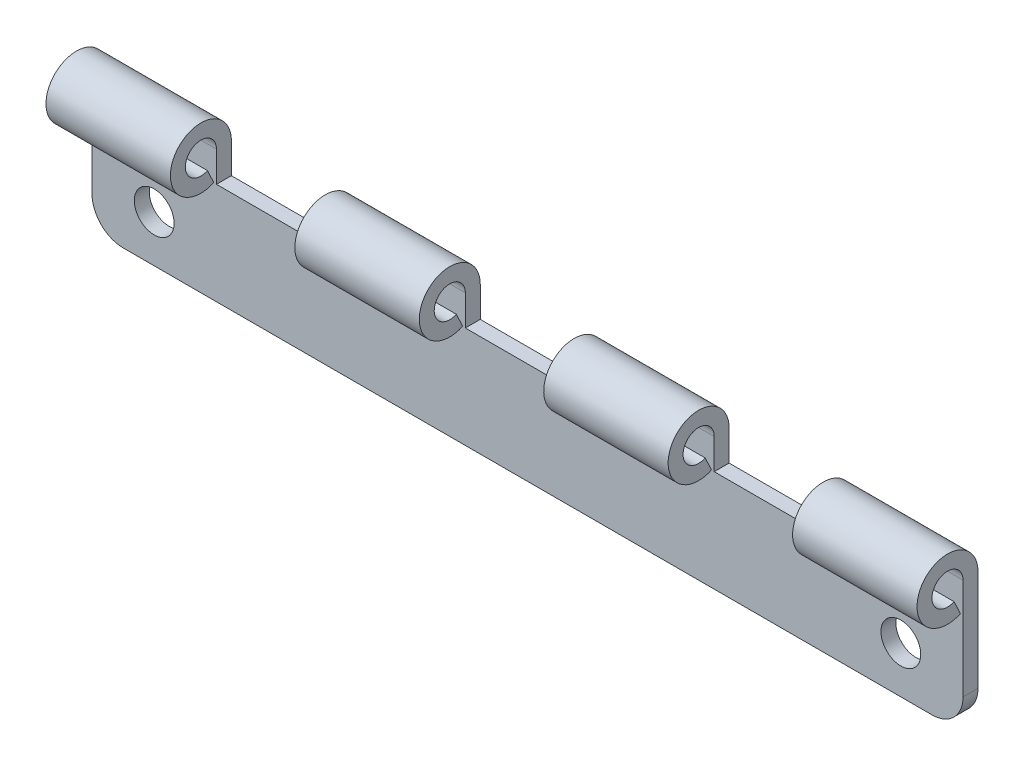
SolidWorks part; units mm, degrees
other "Top Leaf"
other "Bottom Leaf"
other "Pin" parameters "D1"=17.6771, "Angle"=25, "D2"=74.218, "Pin Diameter"=3.175, "D3"=51.2197, "Knuckle Diameter"=28.575, "Leaf Thickness"=1.524, "Overall Width"=26.9875, "Length"=609.6, "Break Line"=101.6, "Knuckle Length"=12.7, "Chamfer"=0.3175
ref_plane "Front Plane" through (0, 0, 0) normal (0, 0, 1) x (1, 0, 0)
ref_plane "Top Plane" through (0, 0, 0) normal (0, 1, 0) x (1, 0, 0)
ref_plane "Right Plane" through (0, 0, 0) normal (1, 0, 0) x (0, 0, -1)
sketch "Sketch1" plane through (0, 0, 0) normal (1, 0, 0) x (0, 0, -1)
  line L0 (3.1115, 0) -> (3.1115, -13.4937) construction
  line L1 (3.1115, -13.4937) -> (1.5875, -13.4937) construction
  line L2 (1.5875, -13.4937) -> (1.5875, -2.6761) construction
  line L3 (0, 1.5875) -> (0, 3.1115) construction
  line L4 (0.6709, 1.4388) -> (1.315, 2.82) construction
  line L5 (0, -1.5875) -> (0, -3.1115) construction
  line L6 (0.6709, -1.4388) -> (1.315, -2.82) construction
  line L7 (3.1115, 0) -> (3.1115, 13.4937) construction
  line L8 (3.1115, 13.4937) -> (1.5875, 13.4937) construction
  line L9 (1.5875, 13.4937) -> (1.5875, 2.6761) construction
  line L10 (0, 3.1115) -> (3.1115, 3.1115) construction
  line L11 (0, -3.1115) -> (3.1115, -3.1115) construction
  line L12 (1.5875, -2.6761) -> (1.5875, 2.6761) construction
  line L13 (1.5875, 3.1369) -> (3.1115, 3.1369) construction
  circle A0 centre (0, 0) radius 1.5875 construction
  circle A1 centre (0, 0) radius 3.1115 construction
  point P3 (0, 1.5875)
  point P4 (0, -1.5875)
  point P5 (-1.5875, 0)
  point P6 (1.5875, 0)
  point P8 (-3.1115, 0)
  point P9 (0, 3.1115)
  point P10 (3.1115, 0)
  point P11 (0, -3.1115)
  point P17 (1.5875, -13.4937)
  point P18 (3.1115, -13.4937)
  point P22 (1.5875, -2.6761)
  point P24 (0.6709, 1.4388)
  point P25 (1.315, 2.82)
  point P30 (0.6709, -1.4388)
  point P31 (1.315, -2.82)
  point P34 (1.5875, 2.6761)
  point P36 (1.5875, 13.4937)
  point P37 (3.1115, 13.4937)
  point P40 (3.1115, -3.1115)
  point P41 (3.1115, 3.1115)
  point P44 (1.5875, 3.1369)
  point P45 (3.1115, 3.1369)
  dimension "D1" = 25
  dimension "Knuckle Diameter" = 6.223
  dimension "D2" = 0.0254
sketch "Sketch2" plane through (0, 0, 0) normal (0, 0, 1) x (1, 0, 0)
  line L0 (304.8, 13.4937) -> (-304.8, 13.4937) construction
  line L2 (304.8, -13.4937) -> (-304.8, -13.4938) construction
  line L4 (-304.8, -13.4938) -> (-304.8, 13.4937) construction
  line L5 (304.8, -13.4937) -> (304.8, 13.4937) construction
  line L6 (304.8, 3.1115) -> (-304.8, 3.1115) construction
  line L7 (-304.8, -3.1115) -> (304.8, -3.1115) construction
  line L8 (304.8, 0) -> (-304.8, 0) construction
  line L9 (203.2, -13.4937) -> (203.2, 13.4937) construction
  line L10 (-203.2, -13.4938) -> (-203.2, 13.4937) construction
  line L11 (0, -13.4937) -> (0, 13.4937) construction
  line L12 (304.8, 2.794) -> (304.4825, 3.1115) construction
  point P4 (0, 13.4937)
  point P9 (0, -13.4937)
  point P10 (-304.8, -13.4938)
  point P12 (-304.8, 13.4937)
  point P13 (304.8, -13.4937)
  point P14 (304.8, 13.4937)
  point P18 (292.1, -3.1115)
  point P19 (-304.8, -3.1115)
  point P20 (-304.8, 3.1115)
  point P21 (304.8, -3.1115)
  point P22 (304.8, 3.1115)
  point P28 (0, 0)
  point P30 (-304.8, 0)
  point P31 (304.8, 0)
  point P34 (203.2, 0)
  point P35 (203.2, -13.4937)
  point P36 (203.2, 13.4937)
  point P39 (-203.2, 0)
  point P40 (-203.2, 13.4937)
  point P41 (-203.2, -13.4938)
  point P44 (0, 0)
  point P45 (279.4, -3.1115)
  point P49 (304.4825, 3.1115)
  point P50 (304.8, 2.794)
  dimension "D1" = 12.7
  dimension "D2" = 45
ref_plane "Plane1" through (304.8, 0, 0) normal (1, 0, 0) x (0, 0, -1)
sketch "Sketch3" plane through (0, 0, 0) normal (1, 0, 0) x (0, 0, -1)
  line L0 (1.5875, 0) -> (1.5875, -2.6761)
  line L2 (0.6709, -1.4388) -> (1.315, -2.82) construction
  line L3 (0.6709, -1.4388) -> (1.315, -2.82)
  line L4 (1.5875, -13.4937) -> (1.5875, -2.6761) construction
  line L5 (1.5875, -13.4937) -> (1.5875, -2.6761)
  line L6 (3.1115, 0) -> (3.1115, -13.4937) construction
  line L7 (3.1115, 0) -> (3.1115, -13.4937)
  line L8 (3.1115, -13.4937) -> (1.5875, -13.4937) construction
  line L9 (3.1115, -13.4937) -> (1.5875, -13.4937)
  circle A0 centre (0, 0) radius 3.1115 construction
  arc A1 (3.1115, 0) -> (1.315, -2.82) centre (0, 0) ccw
  circle A2 centre (0, 0) radius 1.5875 construction
  arc A3 (1.5875, 0) -> (0.6709, -1.4388) centre (0, 0) ccw
extrude "Boss-Extrude1" add sketch "Sketch3" along normal mid plane 609.6
sketch "Sketch4" plane through (0, 0, 0) normal (0, 0, 1) x (1, 0, 0)
  line L0 (292.1, -3.1115) -> (292.1, 3.1115)
  line L1 (304.8, 3.1115) -> (-304.8, 3.1115) construction
  line L2 (292.1, 3.1115) -> (304.8, 3.1115)
  line L3 (304.8, 3.1115) -> (304.8, -3.1115)
  line L4 (304.8, -3.1115) -> (292.1, -3.1115)
extrude "Cut-Extrude1" cut sketch "Sketch4" against normal through all both and the other way through all
pattern_linear "LPattern1" count 24 spacing 25.4 along (-1, 0, 0) of "Cut-Extrude1"
sketch "Sketch5" plane through (304.8, 0, 0) normal (1, 0, 0) x (0, 0, -1)
  line L0 (1.5875, 13.4937) -> (1.5875, 2.6761) construction
  line L1 (3.1115, 0) -> (3.1115, 13.4937) construction
  line L3 (1.5875, 13.4937) -> (1.5875, 2.6761)
  line L4 (3.1115, 0) -> (3.1115, 13.4937)
  line L6 (3.1115, 13.4937) -> (1.5875, 13.4937) construction
  line L7 (3.1115, 13.4937) -> (1.5875, 13.4937)
  line L8 (0.6709, 1.4388) -> (1.315, 2.82) construction
  line L9 (0.6709, 1.4388) -> (1.315, 2.82)
  line L10 (1.5875, 2.6761) -> (1.5875, 0)
  circle A0 centre (0, 0) radius 1.5875 construction
  circle A1 centre (0, 0) radius 3.1115 construction
  arc A2 (0.6709, 1.4388) -> (1.5875, 0) centre (0, 0) ccw
  arc A3 (1.315, 2.82) -> (3.1115, 0) centre (0, 0) ccw
extrude "Boss-Extrude2" add sketch "Sketch5" against normal blind 609.6 separate body
sketch "Sketch6" plane through (0, 0, 0) normal (0, 0, 1) x (1, 0, 0)
  line L0 (279.4, -3.1115) -> (279.4, 3.1115)
  line L1 (304.8, 3.1115) -> (-304.8, 3.1115) construction
  line L2 (279.4, 3.1115) -> (292.1, 3.1115)
  line L3 (292.1, 3.1115) -> (292.1, -3.1115)
  line L4 (292.1, -3.1115) -> (279.4, -3.1115)
extrude "Cut-Extrude2" cut sketch "Sketch6" against normal through all both and the other way through all
pattern_linear "LPattern2" count 24 spacing 25.4 along (-1, 0, 0) of "Cut-Extrude2"
sketch "Sketch7" plane through (304.8, 0, 0) normal (1, 0, 0) x (0, 0, -1)
  circle A0 centre (0, 0) radius 1.5875 construction
  circle A1 centre (0, 0) radius 1.5875
extrude "Boss-Extrude3" add sketch "Sketch7" against normal blind 609.6 separate body
chamfer "Chamfer1" distance 0.3175 angle 45 2 edges at (-304.8, 0, -1.5875) (304.8, 0, -1.5875)
sketch "Sketch8" plane through (-304.8, 0, 0) normal (-1, 0, 0) x (0, 0, 1)
  line L1 (-5.8812, 15.0331) -> (5.8812, 15.0331)
  line L2 (-5.8812, 15.0331) -> (-5.8812, -15.0331)
  line L3 (-5.8812, -15.0331) -> (5.8812, -15.0331)
  line L4 (5.8812, 15.0331) -> (5.8812, -15.0331)
  line L5 (-5.8812, 15.0331) -> (5.8812, -15.0331) construction
  line L6 (-5.8812, -15.0331) -> (5.8812, 15.0331) construction
  point P0 (0, 0)
extrude "Cut-Extrude3" cut sketch "Sketch8" against normal through all from offset 88.9 offset against normal yes
delete or keep bodies "Body-Delete/Keep 1" type delete bodies bodies 185
delete or keep bodies "Body-Delete/Keep 2" type delete bodies bodies 186
fillet "Fillet1" radius 3.175 2 edges at (-304.8, -13.4937, -2.3495) (-215.9, -13.4937, -2.3495)
sketch "Sketch9" plane through (0, 0, -3.1115) normal (0, 0, -1) x (-1, 0, 0)
  line L0 (222.25, -8.7312) -> (298.45, -8.7312) construction
  line L1 (219.075, -13.4937) -> (301.625, -13.4937) construction
  line L2 (304.8, -10.3187) -> (304.8, 0) construction
  circle A0 centre (222.25, -8.7312) radius 2.032
  circle A1 centre (298.45, -8.7312) radius 2.032
  dimension "D2" = 4.064
  dimension "D1" = 76.2
  dimension "D3" = 4.7625
  dimension "D4" = 6.35
extrude "Cut-Extrude4" cut sketch "Sketch9" against normal through all
equation "\"D1@Sketch1\"=\"Angle@Sketch1\""
equation "\"D1@Sketch2\"=\"Knuckle Length@Sketch2\""
equation "\"D1@Boss-Extrude1\" = \"Length@Sketch2\""
equation "\"D1@LPattern1\" = \"Length@Sketch2\" /  ( \"Knuckle Length@Sketch2\" * 2 ) "
equation "\"D3@LPattern1\" = \"Knuckle Length@Sketch2\" * 2"
equation "\"D1@Boss-Extrude2\"=\"Length@Sketch2\""
equation "\"Chamfer@Sketch2\" = \"Pin Diameter@Sketch1\" * .1"
equation "\"D1@Boss-Extrude3\" = \"Length@Sketch2\""
equation "\"D1@Chamfer1\"=\"Chamfer@Sketch2\""
equation "\"D3@LPattern2\" = \"Knuckle Length@Sketch2\" * 2"
equation "\"D1@LPattern2\" = \"Length@Sketch2\" /  ( \"Knuckle Length@Sketch2\" * 2 ) "
